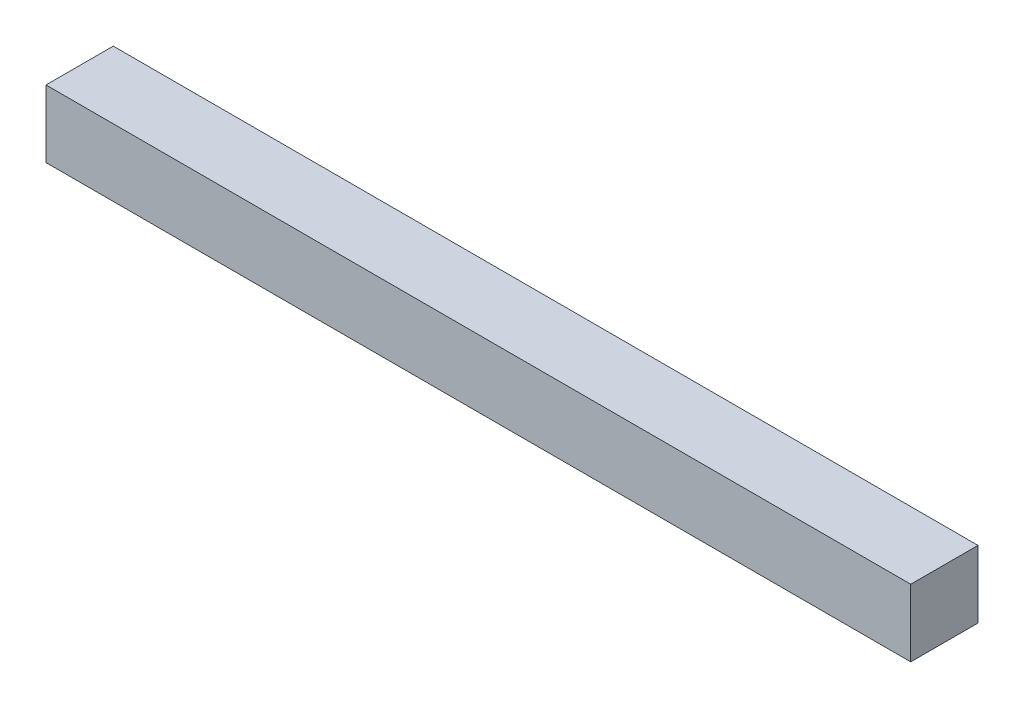
SolidWorks part; units mm, degrees
material "Pine"
ref_plane "X-Y Datum" through (0, 0, 0) normal (0, 0, 1) x (1, 0, 0)
ref_plane "X-Z Datum" through (0, 0, 0) normal (0, 1, 0) x (1, 0, 0)
ref_plane "Y-Z Datum" through (0, 0, 0) normal (1, 0, 0) x (0, 0, -1)
sketch "Sketch1" plane through (0, 0, 0) normal (1, 0, 0) x (0, 0, -1)
  line L1 (-12.7, 12.7) -> (12.7, 12.7)
  line L2 (-12.7, 12.7) -> (-12.7, -12.7)
  line L3 (-12.7, -12.7) -> (12.7, -12.7)
  line L4 (12.7, 12.7) -> (12.7, -12.7)
  line L5 (-12.7, 12.7) -> (12.7, -12.7) construction
  line L6 (-12.7, -12.7) -> (12.7, 12.7) construction
  point P0 (0, 0)
  dimension "D1" = 25.4
extrude "Boss-Extrude1" add sketch "Sketch1" along normal blind 326.5694
